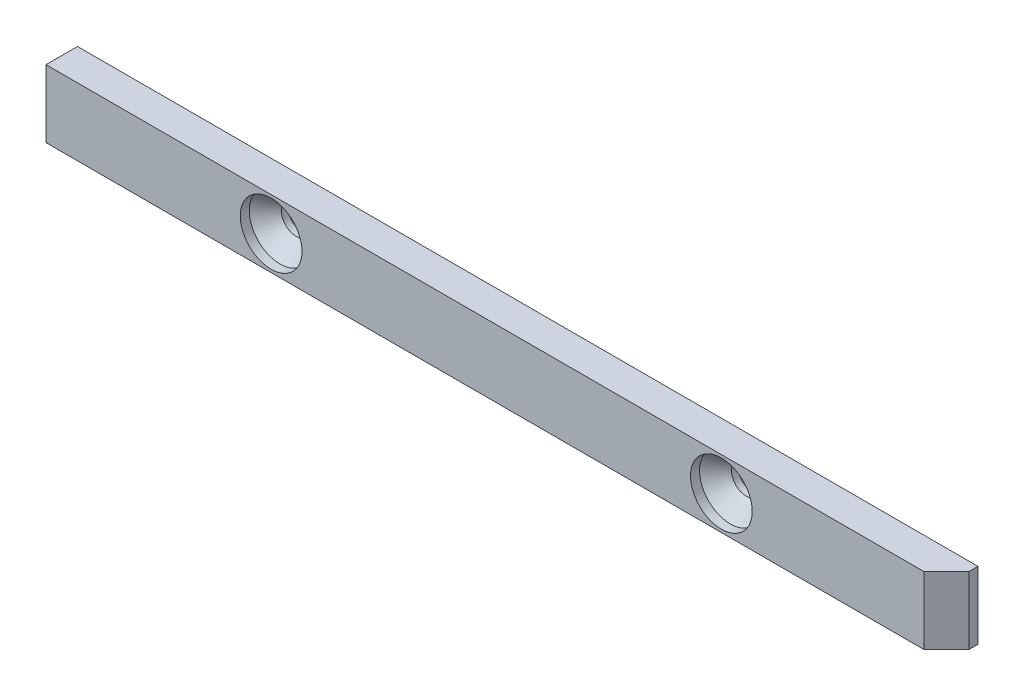
SolidWorks part; units mm, degrees
material "PE1000 Высокой плотности"
ref_plane "Спереди" through (0, 0, 0) normal (0, 0, 1) x (1, 0, 0)
ref_plane "Сверху" through (0, 0, 0) normal (0, 1, 0) x (1, 0, 0)
ref_plane "Справа" through (0, 0, 0) normal (1, 0, 0) x (0, 0, -1)
sketch "Эскиз1" plane through (0, 0, 0) normal (0, 0, 1) x (1, 0, 0)
  line L1 (-100, -7.5) -> (100, -7.5)
  line L2 (-100, -7.5) -> (-100, 7.5)
  line L3 (-100, 7.5) -> (100, 7.5)
  line L4 (100, -7.5) -> (100, 7.5)
  line L5 (-100, -7.5) -> (100, 7.5) construction
  line L6 (-100, 7.5) -> (100, -7.5) construction
  point P0 (0, 0)
  dimension "D1" = 15
  dimension "D2" = 200
extrude "Бобышка-Вытянуть1" add sketch "Эскиз1" along normal blind 7
chamfer "Фаска1" distance 5 angle 45 1 edges at (100, 0, 7)
sketch "Эскиз2" plane through (0, 0, 7) normal (0, 0, 1) x (1, 0, 0)
  line L0 (-100, 0) -> (95, 0) construction
  line L1 (-100, 7.5) -> (-100, -7.5) construction
  line L2 (95, -7.5) -> (95, 7.5) construction
  circle A0 centre (-50, 0) radius 3
  circle A1 centre (50, 0) radius 3
  dimension "D2" = 6
  dimension "D3" = 100
  dimension "D1" = 50
hole_wizard "Зенковка для винта с потайной головкой и внутренним шестигранником M61" positions "Эскиз3" profile "Эскиз4" countersink size "M6" standard "DIN"
sketch "Эскиз3" plane through (0, 0, 7) normal (0, 0, 1) x (1, 0, 0)
  point P0 (-50, 0)
  point P4 (50, 0)
sketch "Эскиз4" plane through (-50, 0, 7) normal (1, 0, 0) x (0, -1, 0)
  line L0 (0, 0) -> (0, 31.9828)
  line L1 (0, 31.9828) -> (3.3, 30)
  line L2 (3.3, 30) -> (3.3, 5.555)
  line L3 (3.3, 5.555) -> (6.855, 2)
  line L4 (6.855, 2) -> (6.855, 0)
  line L6 (6.855, 0) -> (0, 0)
  line L7 (-3.3, 5.555) -> (-6.855, 2) construction
  line L10 (0, 31.9828) -> (-3.3, 30) construction
  line L11 (0, -6.35) -> (0, 107.95) construction
  dimension "Диаметр отверстия" = 6.6
  dimension "Глубина отверстия" = 30
  dimension "Диаметр зенковки" = 13.71
  dimension "Угол зенковки" = 90
  dimension "Угол заточки сверла" = 118
  dimension "Утопленность" = 2
